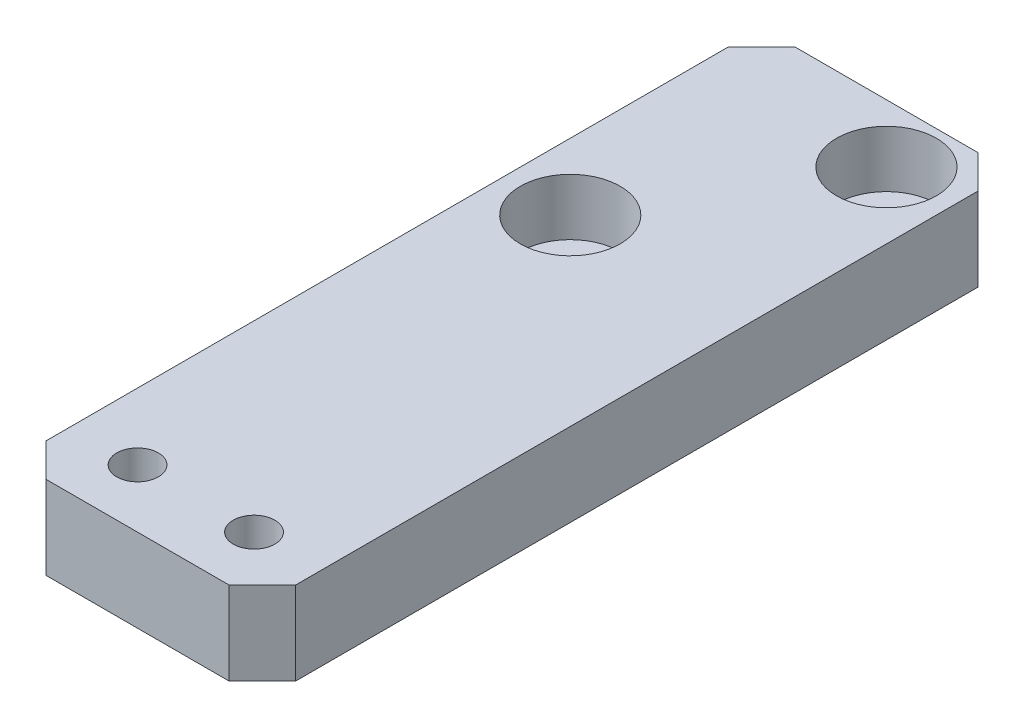
SolidWorks part; units mm, degrees
material "6061 Alloy"
ref_plane "Front Plane" through (0, 0, 0) normal (0, 0, 1) x (1, 0, 0)
ref_plane "Top Plane" through (0, 0, 0) normal (0, 1, 0) x (1, 0, 0)
ref_plane "Right Plane" through (0, 0, 0) normal (1, 0, 0) x (0, 0, -1)
sketch "Sketch1" plane through (0, 0, 0) normal (0, 1, 0) x (1, 0, 0)
  line L1 (7.5, -22.5) -> (-7.5, -22.5)
  line L2 (7.5, -22.5) -> (7.5, 22.5)
  line L3 (7.5, 22.5) -> (-7.5, 22.5)
  line L4 (-7.5, -22.5) -> (-7.5, 22.5)
  line L5 (7.5, -22.5) -> (-7.5, 22.5) construction
  line L6 (7.5, 22.5) -> (-7.5, -22.5) construction
  point P0 (0, 0)
  dimension "D1" = 15
  dimension "D2" = 45
extrude "Boss-Extrude1" add sketch "Sketch1" along normal blind 5 contours L3 L4 L1 L2
sketch "Sketch4" plane through (0, 5, 0) normal (0, 1, 0) x (1, 0, 0)
  line L0 (-3.5, -19) -> (3.5, 19) construction
  point P0 (-3.5, -19)
  point P2 (3.5, 19)
  dimension "D1" = 38
  dimension "D2" = 7
hole_wizard "M3 Tapped Hole1" positions "Sketch5" profile "Sketch6" tap size "M3" standard "GB"
sketch "Sketch5" plane through (0, 5, 0) normal (0, 1, 0) x (1, 0, 0)
  line L0 (0, -2.75) -> (0, 2.75) construction
  point P0 (-3.5, -19)
  point P8 (3.5, -19)
sketch "Sketch6" plane through (-3.5, 5, 19) normal (1, 0, 0) x (0, 0, 1)
  line L0 (0, 0) -> (0, 4.7511)
  line L1 (0, 4.7511) -> (1.25, 4)
  line L2 (1.25, 4) -> (1.25, 0)
  line L5 (1.25, 0) -> (0, 0)
  line L10 (0, 4.7511) -> (-1.25, 4) construction
  line L11 (0, -6.35) -> (0, 107.95) construction
  dimension "Tap Drill Dia." = 2.5
  dimension "Tap Drill Depth" = 4
  dimension "Drill Angle" = 118
cosmetic thread "Hole Thread1" parameters "D1"=4.5, "D2"=3
cosmetic thread "Hole Thread2" parameters "D1"=4.5, "D2"=3
hole_wizard "CBORE for M3 Hexagon socket head cap screws1" positions "Sketch8" profile "Sketch10" counterbore size "M3" standard "GB" end condition through all
sketch "Sketch8" plane through (0, 5, 0) normal (0, 1, 0) x (1, 0, 0)
  point P0 (3.5, 19)
  point P3 (-3.5, 7)
  dimension "D1" = 7
  dimension "D2" = 12
sketch "Sketch10" plane through (3.5, 5, -19) normal (1, 0, 0) x (0, 0, 1)
  line L0 (0, 0) -> (0, 5)
  line L1 (0, 5) -> (1.7, 5)
  line L3 (1.7, 5) -> (1.7, 3.4)
  line L4 (1.7, 3.4) -> (3, 3.4)
  line L5 (3, 3.4) -> (3, 0)
  line L7 (3, 0) -> (0, 0)
  line L11 (0, -6.35) -> (0, 107.95) construction
  dimension "Thru Hole Dia." = 3.4
  dimension "Thru Hole Depth" = 5
  dimension "C'Bore Dia." = 6
  dimension "C'Bore Depth" = 3.4
chamfer "Chamfer1" distance 2 angle 45 4 edges at (7.5, 2.5, -22.5) (-7.5, 2.5, -22.5) (7.5, 2.5, 22.5) (-7.5, 2.5, 22.5)
